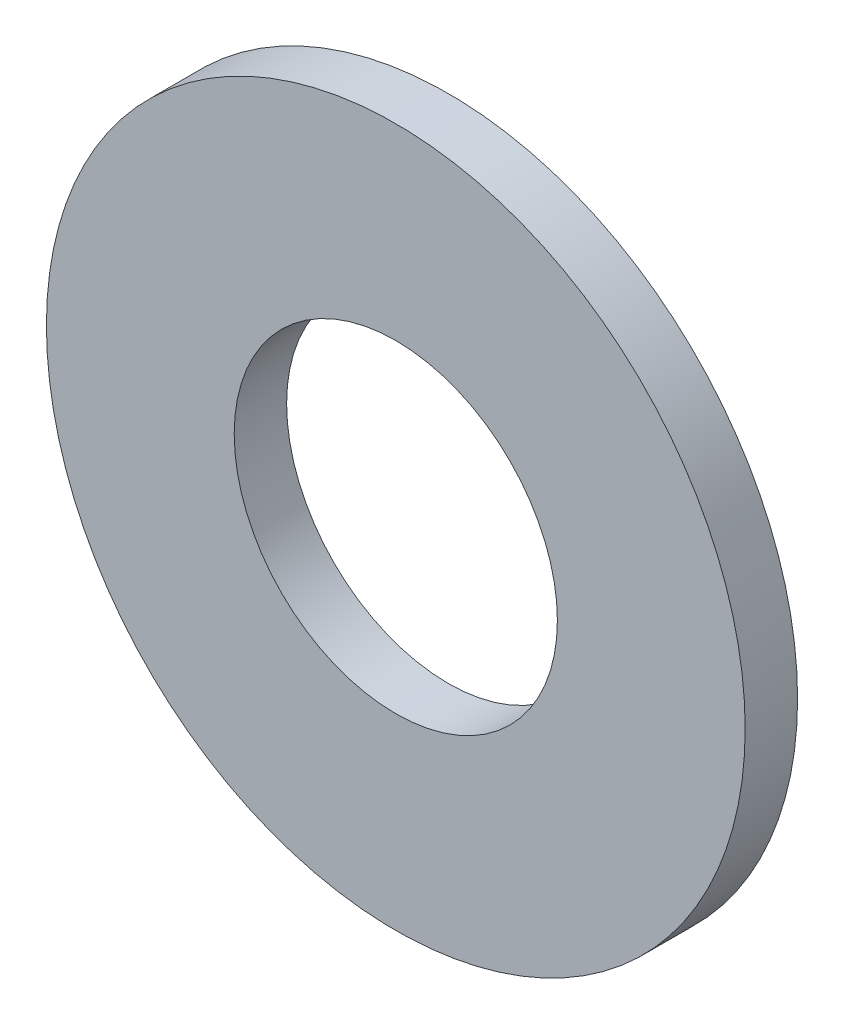
SolidWorks part; units mm, degrees
material "Ductile Iron"
ref_plane "Front Plane" through (0, 0, 0) normal (0, 0, 1) x (1, 0, 0)
ref_plane "Top Plane" through (0, 0, 0) normal (0, 1, 0) x (1, 0, 0)
ref_plane "Right Plane" through (0, 0, 0) normal (1, 0, 0) x (0, 0, -1)
sketch "Sketch1" plane through (0, 0, 0) normal (0, 0, 1) x (1, 0, 0)
  circle A0 centre (0, 0) radius 20
  circle A1 centre (0, 0) radius 9.25
  dimension "D1" = 40
  dimension "D2" = 18.5
extrude "Boss-Extrude1" add sketch "Sketch1" along normal blind 3
